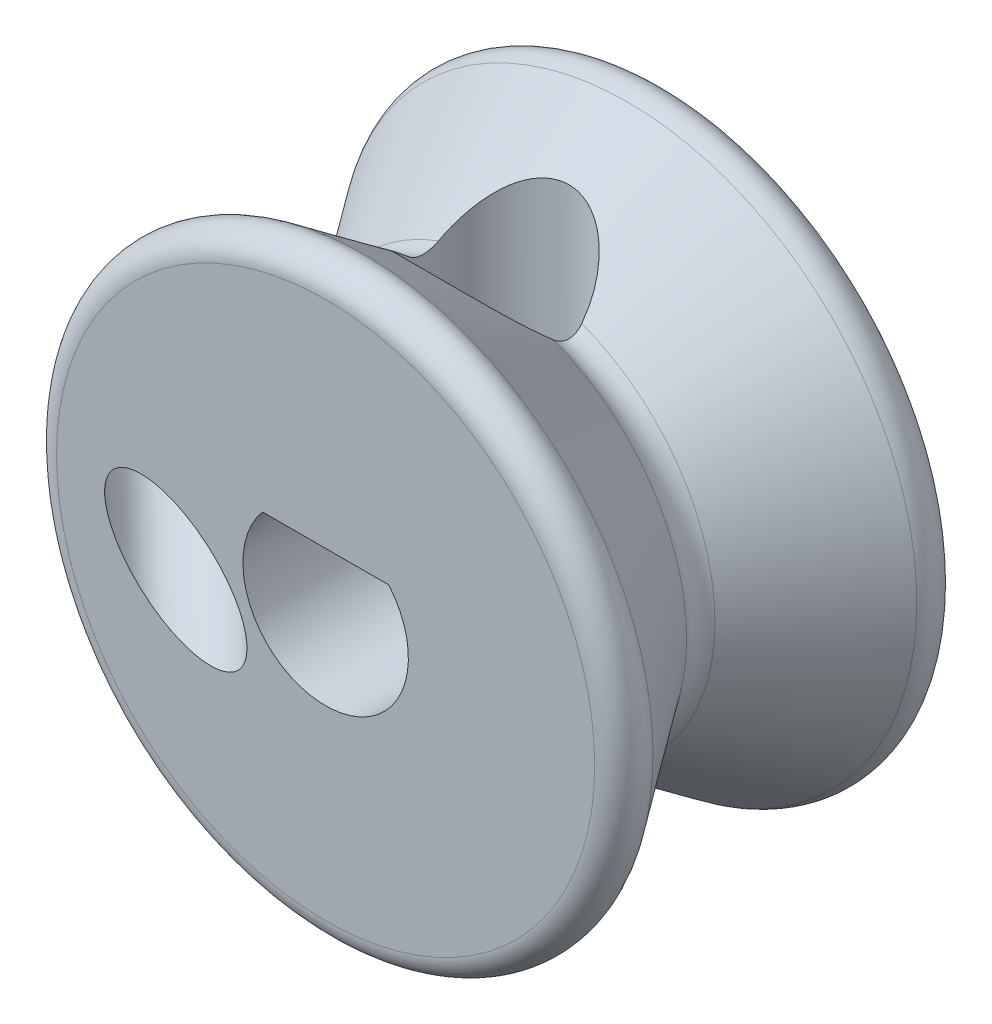
SolidWorks part; units mm, degrees
ref_plane "Front Plane" through (0, 0, 0) normal (0, 0, 1) x (1, 0, 0)
ref_plane "Top Plane" through (0, 0, 0) normal (0, 1, 0) x (1, 0, 0)
ref_plane "Right Plane" through (0, 0, 0) normal (1, 0, 0) x (0, 0, -1)
sketch "Sketch3" plane through (0, 0, 0) normal (1, 0, 0) x (0, 0, -1)
  line L0 (0, 0) -> (7, 0)
  line L1 (0, 0) -> (0, 5.5284)
  line L3 (0.7906, 5.9353) -> (3.2094, 4.2076)
  line L4 (3.7906, 4.2076) -> (6.2094, 5.9353)
  line L5 (7, 5.5284) -> (7, 0)
  arc A0 (6.2094, 5.9353) -> (7, 5.5284) centre (6.5, 5.5284) cw
  arc A1 (3.2094, 4.2076) -> (3.7906, 4.2076) centre (3.5, 4.6145) ccw
  arc A2 (0, 5.5284) -> (0.7906, 5.9353) centre (0.5, 5.5284) cw
  point P9 (3.5, 0)
  point P13 (7, 6.5)
  point P16 (3.5, 4)
  point P19 (0, 6.5)
  dimension "D4" = 0.5
  dimension "D1" = 7
  dimension "D2" = 6.5
  dimension "D3" = 4
revolve "Revolve1" add sketch "Sketch3" angle 360 about L0
sketch "Sketch4" plane through (0, 0, 0) normal (0, 0, 1) x (1, 0, 0)
  line L0 (-1.2961, 1.1) -> (1.2961, 1.1)
  arc A0 (-1.2961, 1.1) -> (1.2961, 1.1) centre (0, 0) ccw
  dimension "D1" = 3.4
  dimension "D2" = 1.1
extrude "Cut-Extrude1" cut sketch "Sketch4" against normal blind 7
sketch "Sketch5" plane through (0, 1.1, 0) normal (0, -1, 0) x (1, 0, 0)
  line L0 (0, 0) -> (0, -7) construction
  line L1 (-5.5284, -7) -> (5.5284, -7) construction
  circle A0 centre (0, -3.5) radius 1.5
  dimension "D1" = 3
extrude "Cut-Extrude2" cut sketch "Sketch5" against normal blind 7 and the other way blind 0.5
ref_plane "Plane2" through (-3.7195, 3.1566, -2.2703) normal (-0.6204, 0.5265, -0.5812) x (-0.4225, 0.4, 0.8133)
sketch "Sketch6" plane through (-3.7195, 3.1566, -2.2703) normal (-0.6204, 0.5265, -0.5812) x (-0.4225, 0.4, 0.8133)
  circle A0 centre (-0.0146, -2.6175) radius 1
  ellipse E0 centre (-3.5979, 0.1137) end of major axis (-3.7307, -4.0918) minor radius 2.4456 (-2.643, 4.0431) -> (-1.3995, 2.0985) ccw construction
  dimension "D1" = 2
  dimension "D2" = 3.5832
  dimension "D3" = 4.716
extrude "Cut-Extrude3" cut sketch "Sketch6" against normal through all
